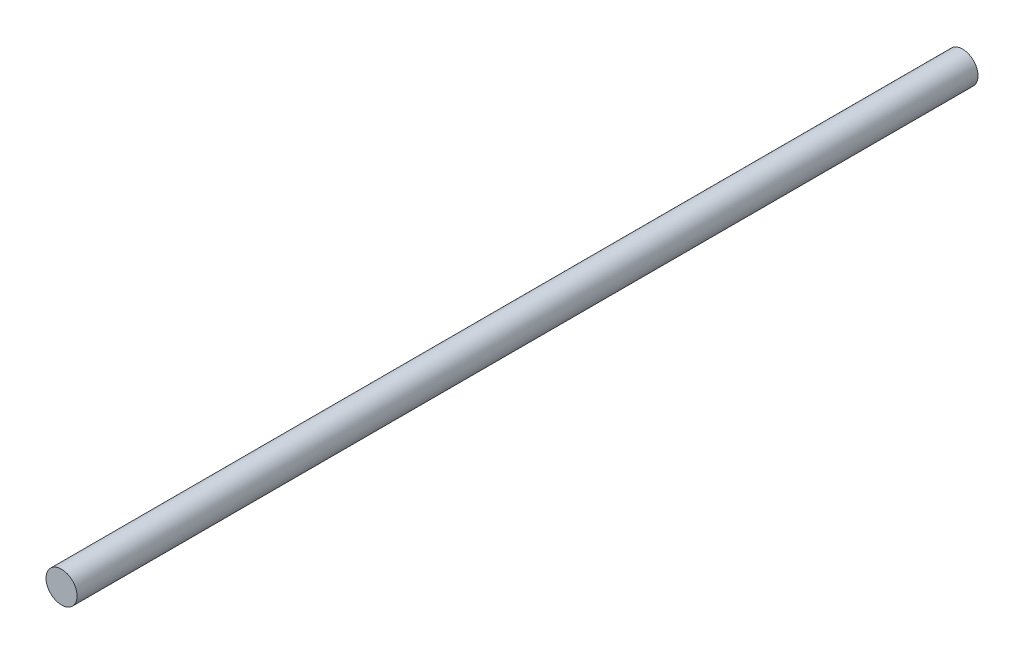
SolidWorks part; units mm, degrees
ref_plane "Front Plane" through (0, 0, 0) normal (0, 0, 1) x (1, 0, 0)
ref_plane "Top Plane" through (0, 0, 0) normal (0, 1, 0) x (1, 0, 0)
ref_plane "Right Plane" through (0, 0, 0) normal (1, 0, 0) x (0, 0, -1)
sketch "Sketch1" plane through (0, 0, 0) normal (0, 0, 1) x (1, 0, 0)
  circle A0 centre (0, 0) radius 1
  dimension "D1" = 2
extrude "Boss-Extrude1" add sketch "Sketch1" along normal blind 58
